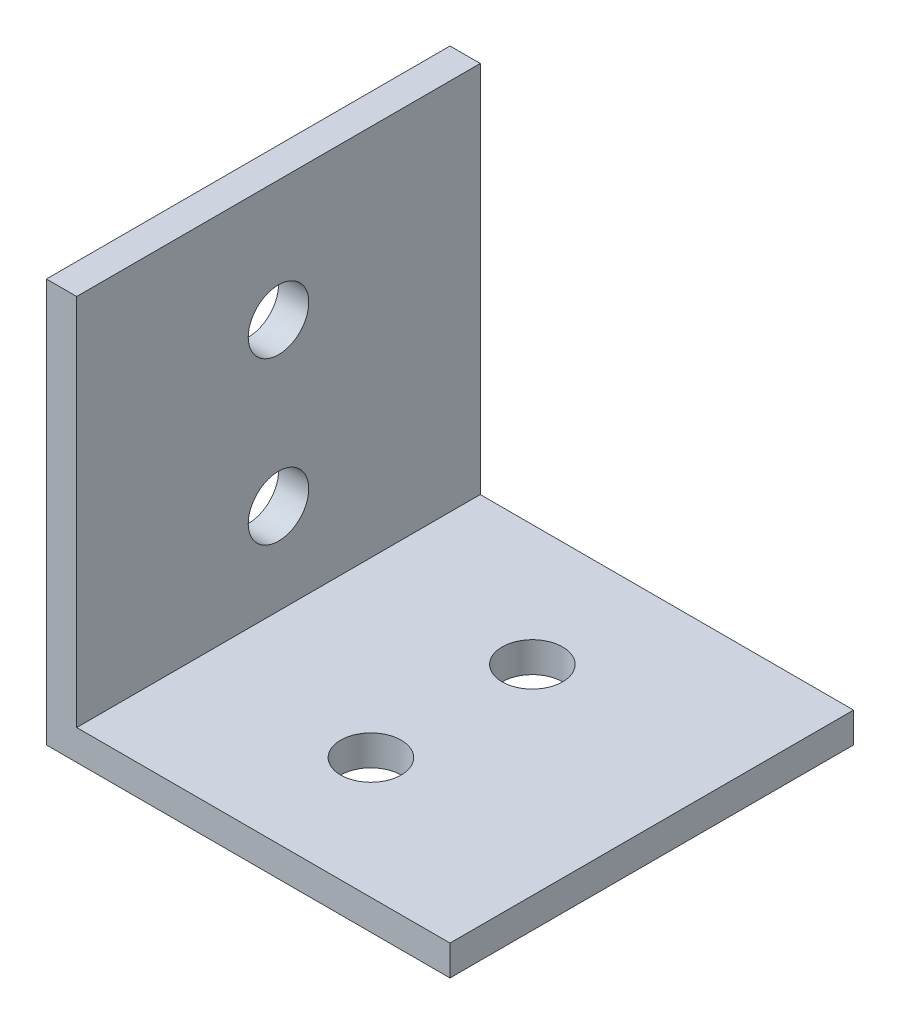
SolidWorks part; units mm, degrees
ref_plane "Plan de face" through (0, 0, 0) normal (0, 0, 1) x (1, 0, 0)
ref_plane "Plan de dessus" through (0, 0, 0) normal (0, 1, 0) x (1, 0, 0)
ref_plane "Plan de droite" through (0, 0, 0) normal (1, 0, 0) x (0, 0, -1)
sketch "Esquisse1" plane through (0, 0, 0) normal (0, 0, 1) x (1, 0, 0)
  line L0 (-18.7143, 3.4981) -> (-18.7143, -16.5019)
  line L1 (-18.7143, -16.5019) -> (1.2857, -16.5019)
  line L2 (1.2857, -16.5019) -> (1.2857, -15.0019)
  line L3 (1.2857, -15.0019) -> (-17.2143, -15.0019)
  line L4 (-17.2143, -15.0019) -> (-17.2143, 3.4981)
  line L5 (-17.2143, 3.4981) -> (-18.7143, 3.4981)
  dimension "D1" = 1.5
  dimension "D2" = 1.5
  dimension "D3" = 20
  dimension "D4" = 20
extrude "Extrusion1" add sketch "Esquisse1" along normal blind 20
sketch "Esquisse2" plane through (0, -15.0019, 0) normal (0, 1, 0) x (-1, 0, 0)
  line L0 (-1.2857, 20) -> (17.2143, 20) construction
  circle A0 centre (8.6337, 14) radius 1.5
  circle A1 centre (8.6337, 6) radius 1.5
  dimension "D1" = 8
  dimension "D2" = 6
extrude "Extrusion2" cut sketch "Esquisse2" against normal blind 20
sketch "Esquisse3" plane through (-18.7143, 0, 0) normal (-1, 0, 0) x (0, 0, 1)
  line L0 (10, -10.5019) -> (10, -2.5019) construction
  line L3 (20, 3.4981) -> (20, -16.5019) construction
  line L4 (20, -16.5019) -> (0, -16.5019) construction
  circle A0 centre (10, -10.5019) radius 1.5
  circle A1 centre (10, -2.5019) radius 1.5
  dimension "D1" = 10
  dimension "D2" = 6
  dimension "D3" = 8
extrude "Extrusion3" cut sketch "Esquisse3" against normal blind 10
